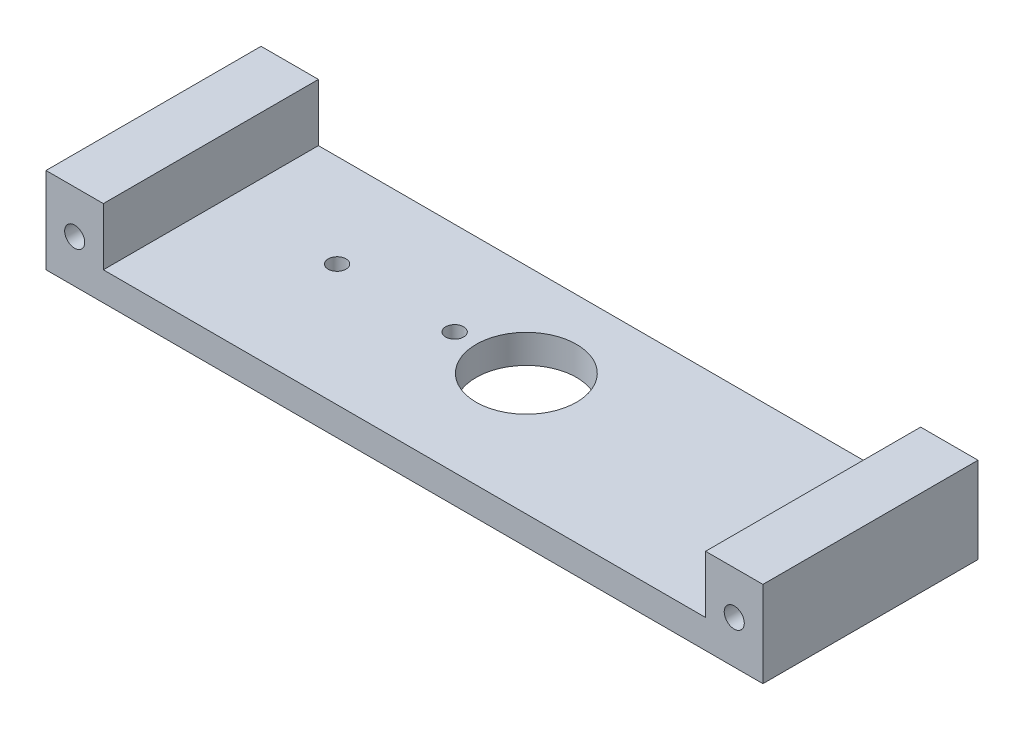
SolidWorks part; units mm, degrees
ref_plane "Front Plane" through (0, 0, 0) normal (0, 0, 1) x (1, 0, 0)
ref_plane "Top Plane" through (0, 0, 0) normal (0, 1, 0) x (1, 0, 0)
ref_plane "Right Plane" through (0, 0, 0) normal (1, 0, 0) x (0, 0, -1)
sketch "Sketch1" plane through (0, 0, 0) normal (0, 1, 0) x (1, 0, 0)
  line L1 (-64.8854, 14.6552) -> (-14.8854, 14.6552)
  line L2 (-64.8854, 14.6552) -> (-64.8854, -0.3448)
  line L3 (-64.8854, -0.3448) -> (-14.8854, -0.3448)
  line L4 (-14.8854, 14.6552) -> (-14.8854, -0.3448)
  line L5 (-64.8854, 14.6552) -> (-14.8854, -0.3448) construction
  line L6 (-64.8854, -0.3448) -> (-14.8854, 14.6552) construction
  point P0 (-39.8854, 7.1552)
  dimension "D1" = 15
  dimension "D2" = 50
extrude "Boss-Extrude1" add sketch "Sketch1" along normal blind 2
sketch "Sketch2" plane through (0, 2, 0) normal (0, 1, 0) x (1, 0, 0)
  line L0 (-39.8854, 8.1552) -> (-44.8854, 8.1552) construction
  line L1 (-64.8854, -0.3448) -> (-14.8854, -0.3448) construction
  circle A0 centre (-39.8854, 8.1552) radius 3.5
  dimension "D7" = 8.5
  dimension "D1" = 5
extrude "Cut-Extrude1" cut sketch "Sketch2" against normal blind 2
sketch "Sketch3" plane through (0, 2, 0) normal (0, 1, 0) x (1, 0, 0)
  line L1 (-14.8854, 14.6552) -> (-64.8854, 14.6552) construction
  line L7 (-64.8854, 14.6552) -> (-60.8854, 14.6552)
  line L13 (-14.8854, 14.6552) -> (-18.8854, 14.6552)
  line L14 (-60.8854, 14.6552) -> (-60.8854, -0.3448)
  line L15 (-64.8854, -0.3448) -> (-14.8854, -0.3448) construction
  line L16 (-60.8854, -0.3448) -> (-64.8854, -0.3448)
  line L17 (-64.8854, -0.3448) -> (-64.8854, 14.6552)
  line L18 (-18.8854, 14.6552) -> (-18.8854, -0.3448)
  line L19 (-18.8854, -0.3448) -> (-14.8854, -0.3448)
  line L20 (-14.8854, -0.3448) -> (-14.8854, 14.6552)
  dimension "D2" = 4
  dimension "D4" = 4
extrude "Boss-Extrude2" add sketch "Sketch3" along normal blind 4
sketch "Sketch4" plane through (0, 0, -14.6552) normal (0, 0, -1) x (-1, 0, 0)
  line L2 (62.8854, 6) -> (62.8854, 0) construction
  line L3 (60.8854, 6) -> (64.8854, 6) construction
  line L4 (14.8854, 0) -> (64.8854, 0) construction
  line L5 (16.8854, 6) -> (16.8854, 0) construction
  line L6 (14.8854, 6) -> (18.8854, 6) construction
  circle A1 centre (62.8854, 3) radius 0.7
  circle A2 centre (16.8854, 3) radius 0.7
  dimension "D1" = 1.4
  dimension "D3" = 1.4
  dimension "D2" = 3
  dimension "D4" = 3
extrude "Cut-Extrude2" cut sketch "Sketch4" against normal through all
hole_wizard "M1.6x0.35 Tapped Hole2" positions "Sketch28" profile "Sketch19" tap size "M1.6x0.35" standard "ANSI Metric" end condition through all
sketch "Sketch28" plane through (0, 2, 0) normal (0, 1, 0) x (1, 0, 0)
  point P0 (-44.8854, 8.1552)
sketch "Sketch19" plane through (-44.8854, 2, -8.1552) normal (1, 0, 0) x (0, 0, 1)
  line L0 (0, 0) -> (0, 2)
  line L1 (0, 2) -> (0.625, 2)
  line L2 (0.625, 2) -> (0.625, 0)
  line L5 (0.625, 0) -> (0, 0)
  line L11 (0, -6.35) -> (0, 107.95) construction
  dimension "Thru Tap Drill Dia." = 1.25
  dimension "Thru Tap Drill Depth" = 2
sketch "Sketch21" plane through (0, 2, 0) normal (0, 1, 0) x (1, 0, 0)
  line L0 (-39.8854, 8.1552) -> (-53.0838, 8.1552) construction
  point P5 (0, 0)
hole_wizard "M1.6x0.35 Tapped Hole1" positions "Sketch27" profile "Sketch24" tap size "M1.6x0.35" standard "ANSI Metric" end condition through all
sketch "Sketch27" plane through (0, 2, 0) normal (0, 1, 0) x (1, 0, 0)
  point P0 (-53.0838, 8.1552)
sketch "Sketch24" plane through (-53.0838, 2, -8.1552) normal (1, 0, 0) x (0, 0, 1)
  line L0 (0, 0) -> (0, 2)
  line L1 (0, 2) -> (0.625, 2)
  line L2 (0.625, 2) -> (0.625, 0)
  line L5 (0.625, 0) -> (0, 0)
  line L11 (0, -6.35) -> (0, 107.95) construction
  dimension "Thru Tap Drill Dia." = 1.25
  dimension "Thru Tap Drill Depth" = 2
